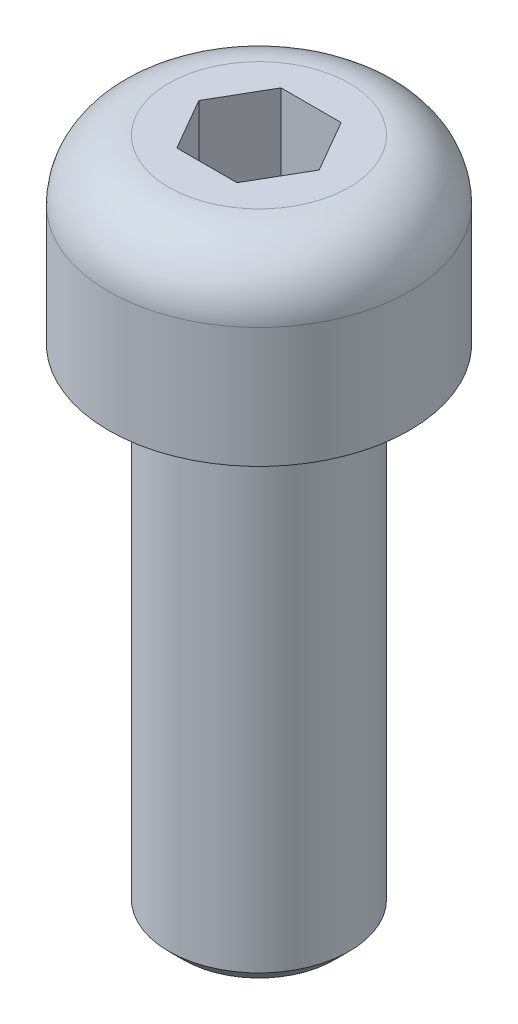
SolidWorks part; units mm, degrees
material "Cast Carbon Steel"
ref_plane "Front Plane" through (0, 0, 0) normal (0, 0, 1) x (1, 0, 0)
ref_plane "Top Plane" through (0, 0, 0) normal (0, 1, 0) x (1, 0, 0)
ref_plane "Right Plane" through (0, 0, 0) normal (1, 0, 0) x (0, 0, -1)
sketch "Sketch1" plane through (0, 0, 0) normal (0, 1, 0) x (1, 0, 0)
  circle A0 centre (0, 0) radius 1.5
  dimension "D1" = 3
extrude "Boss-Extrude1" add sketch "Sketch1" along normal blind 8.25
sketch "Sketch2" plane through (0, 8.25, 0) normal (0, 1, 0) x (1, 0, 0)
  circle A0 centre (0, 0) radius 2.5
  dimension "D1" = 5
extrude "Boss-Extrude2" add sketch "Sketch2" along normal blind 3
fillet "Fillet1" radius 1 1 edges at (0, 11.25, 2.5)
chamfer "Chamfer1" distance 0.25 angle 45 1 edges at (0, 0, 1.5)
sketch "Sketch3" plane through (0, 11.25, 0) normal (0, 1, 0) x (1, 0, 0)
  line L1 (-1, 0) -> (-0.5, -0.866)
  line L2 (-0.5, -0.866) -> (0.5, -0.866)
  line L3 (0.5, -0.866) -> (1, 0)
  line L4 (1, 0) -> (0.5, 0.866)
  line L5 (0.5, 0.866) -> (-0.5, 0.866)
  line L6 (-0.5, 0.866) -> (-1, 0)
  circle A0 centre (0, 0) radius 0.866 construction
  dimension "D1" = 1
extrude "Cut-Extrude1" cut sketch "Sketch3" against normal blind 2
